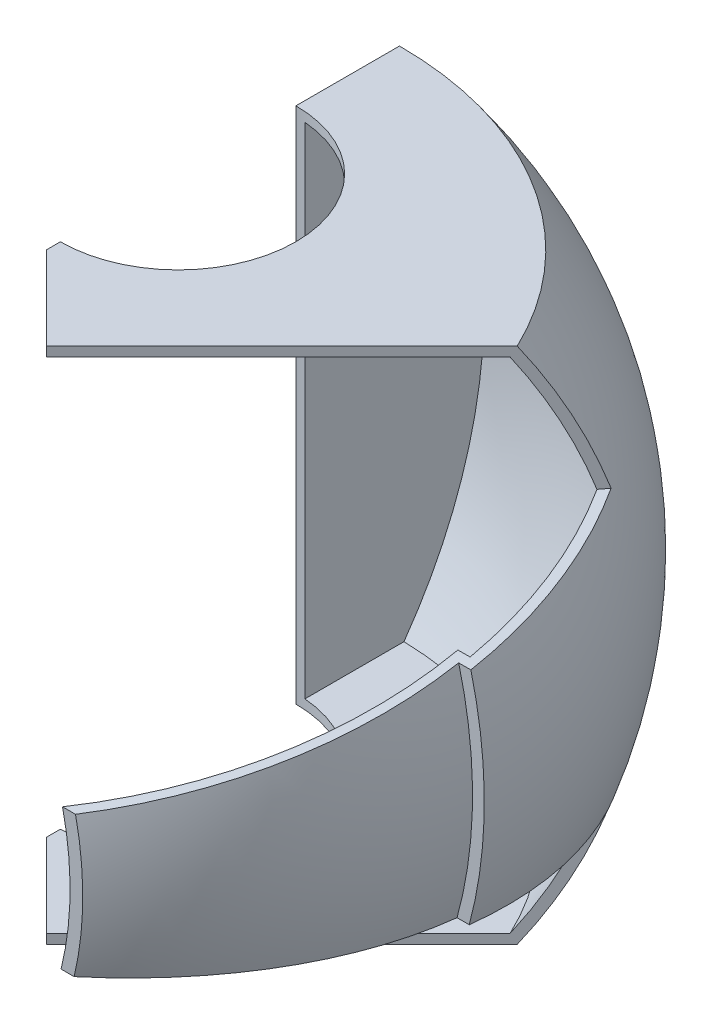
SolidWorks part; units mm, degrees
ref_plane "Płaszczyzna przednia" through (0, 0, 0) normal (0, 0, 1) x (1, 0, 0)
ref_plane "Płaszczyzna górna" through (0, 0, 0) normal (0, 1, 0) x (1, 0, 0)
ref_plane "Płaszczyzna prawa" through (0, 0, 0) normal (1, 0, 0) x (0, 0, -1)
sketch "Szkic1" plane through (0, 0, 0) normal (1, 0, 0) x (0, 0, -1)
  line L0 (0, 0) -> (-111.097, 0) construction
  line L1 (0, -55) -> (0, 55)
  line L2 (0, 55) -> (-75, 55)
  line L3 (0, -55) -> (-75, -55)
  arc A0 (-75, 55) -> (-75, -55) centre (0, 0) ccw
  point P3 (0, 0)
  point P8 (-111.097, 0)
  dimension "D1" = 55
  dimension "D2" = 75
revolve "Obrót1" add sketch "Szkic1" angle 180 about L1
sketch "Szkic2" plane through (0, -55, 0) normal (0, -1, 0) x (1, 0, 0)
  line L0 (0, 0) -> (0, 40)
  line L1 (0, 75) -> (0, -75) construction
  line L2 (0, 40) -> (12.2873, 48.6036)
  line L3 (12.2873, 48.6036) -> (12.2873, 73.9866)
  line L4 (0, 0) -> (17.6777, 17.6777)
  line L5 (17.6777, 17.6777) -> (87.3537, -51.9984)
  line L7 (-26.0659, 75) -> (-26.0659, -104.7585)
  line L8 (-26.0659, -104.7585) -> (87.3537, -104.7585)
  line L9 (87.3537, -104.7585) -> (87.3537, -51.9984)
  line L10 (0, 0) -> (-50.1404, 0)
  line L11 (-50.1404, 0) -> (-50.1404, 112.3931)
  line L12 (-50.1404, 112.3931) -> (99.7171, 112.3931)
  line L13 (99.7171, 112.3931) -> (99.7171, -51.9984)
  line L14 (99.7171, -51.9984) -> (87.3537, -51.9984)
  line L16 (0, 75) -> (-26.0659, 75)
  arc A0 (0, -75) -> (0, 75) centre (0, 0) ccw construction
  arc A1 (67.6777, -32.3223) -> (0, 75) centre (0, 0) ccw
  point P7 (12.2873, 73.9866)
  arc M10 (0, -75) -> (0, 75) centre (0, 0) ccw
  dimension "D1" = 40
  dimension "D2" = 125
  dimension "D3" = 15
  dimension "D4" = 25
  dimension "D5" = 45
extrude "Wytnij-wyciągnięcie6" cut sketch "Szkic2" against normal through all contours L16 L5 L14 L13 L12 L11 L10 L7 M10
sketch "Szkic6" plane through (0, -55, 0) normal (0, -1, 0) x (1, 0, 0)
  line L0 (0, 0) -> (17.6777, 17.6777) construction
  line L1 (0, 75) -> (0, -75)
  line L2 (0, 75) -> (0, 0)
  line L3 (17.6777, 17.6777) -> (87.3537, -51.9984) construction
  line L4 (0, 0) -> (17.6777, 17.6777)
  line L5 (17.6777, 17.6777) -> (87.3537, -51.9984)
  line L6 (0, 0) -> (0, 75)
  arc A2 (0, -75) -> (67.6777, -32.3223) centre (0, 0) ccw
  arc A3 (67.6777, -32.3223) -> (0, 75) centre (0, 0) ccw
  arc A5 (67.6777, -32.3223) -> (0, 75) centre (0, 0) ccw
  arc M5 (67.6777, -32.3223) -> (0, 75) centre (0, 0) ccw
  line M6 (0, 75) -> (0, -75)
  dimension "D1" = 0
extrude "Wytnij-wyciągnięcie7" cut sketch "Szkic6" against normal through all contours L4 L5 M5 M6
ref_plane "Płaszczyzna2" through (100, 0, 0) normal (1, 0, 0) x (0, 0, -1)
sketch "Szkic7" plane through (100, 0, 0) normal (1, 0, 0) x (0, 0, -1)
  line L0 (-60, -15.6538) -> (-60, 14.3462)
  line L1 (45.6666, -30.6538) -> (45.6666, 29.3462)
  line L2 (45.6666, 29.3462) -> (-60, 14.3462)
  line L3 (45.6666, -30.6538) -> (-60, -15.6538)
  dimension "D1" = 60
extrude "Dodanie-wyciągnięcie2" add sketch "Szkic7" against normal up to surface (100 mm away) contours L0 L2 L1 L3
sketch "Szkic8" plane through (0, 0, 0) normal (1, 0, 0) x (0, 0, -1)
  line L0 (-74.9933, 55) -> (-155.5635, 55)
  line L1 (-74.9933, -55) -> (-155.5635, -55)
  line L2 (0, 0) -> (0, 79.5487)
  arc A0 (-74.9933, 55) -> (-74.9933, -55) centre (0, 0) ccw
  arc A1 (-155.5635, 55) -> (-155.5635, -55) centre (0, 0) ccw
  dimension "D1" = 186
  dimension "D2" = 330
revolve "Wycięcie-obrót1" cut sketch "Szkic8" angle 360 about L2
sketch "Szkic9" plane through (0, -55, 0) normal (0, -1, 0) x (1, 0, 0)
  line L0 (0, 0) -> (84.2818, 84.2818)
  line L1 (84.2818, 84.2818) -> (-46.6915, 84.2818)
  line L2 (-46.6915, 84.2818) -> (-46.6915, 0)
  line L3 (0, 0) -> (-50.1404, 0) construction
  line L4 (-46.6915, 0) -> (0, 0)
extrude "Wytnij-wyciągnięcie8" cut sketch "Szkic9" against normal through all
sketch "Szkic10" plane through (0, 0, 0) normal (1, 0, 0) x (0, 0, -1)
  line L0 (-71.8697, 55) -> (-106.6536, 55)
  line L1 (-71.8697, -55) -> (-106.6536, -55)
  line L2 (0, 0) -> (0, 69.3948) construction
  arc A0 (-71.8697, 55) -> (-71.8697, -55) centre (0, 0) ccw
  arc A1 (-106.6536, 55) -> (-106.6536, -55) centre (0, 0) ccw
revolve "Wycięcie-obrót2" cut sketch "Szkic10" angle 90 about L2
sketch "Szkic11" plane through (0, -55, 0) normal (0, -1, 0) x (1, 0, 0)
  line L0 (0, 0) -> (0, -28)
  line L1 (0, 0) -> (0, -74.9933) construction
  circle A0 centre (0, -28) radius 25
  line M5 (0, 0) -> (0, -74.9933)
  dimension "D1" = 28
extrude "Wytnij-wyciągnięcie9" cut sketch "Szkic11" against normal through all contours L0 A0 M5 | A0 L0 M5
shell "Skorupa2" thickness 2
